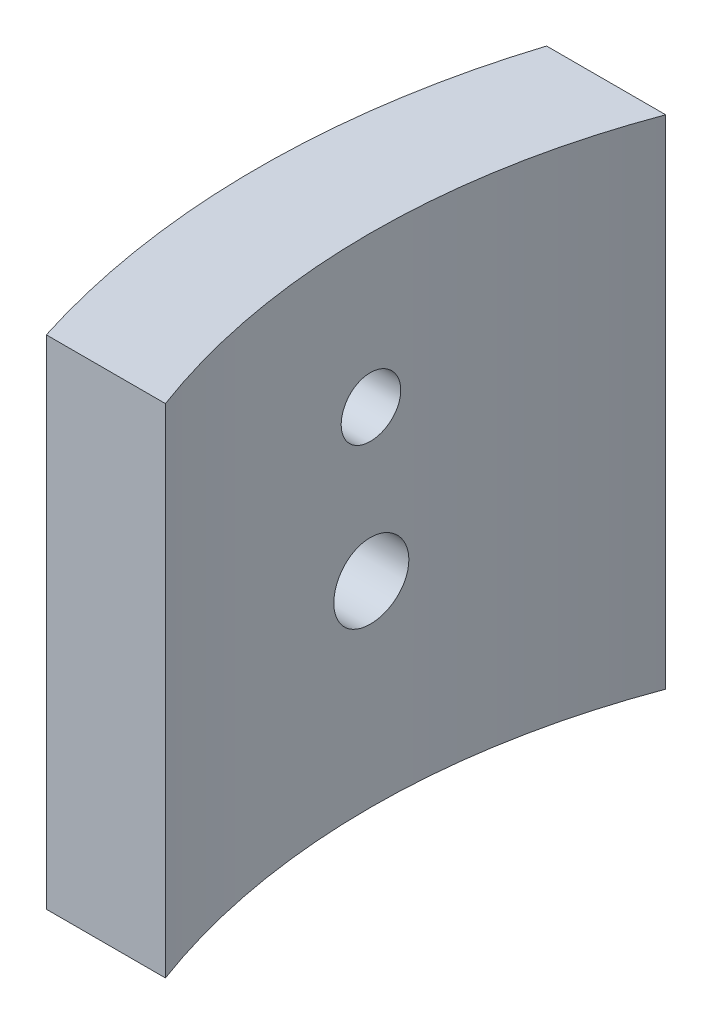
SolidWorks part; units mm, degrees
material "ABS"
ref_plane "Front Plane" through (0, 0, 0) normal (0, 0, 1) x (1, 0, 0)
ref_plane "Top Plane" through (0, 0, 0) normal (0, 1, 0) x (1, 0, 0)
ref_plane "Right Plane" through (0, 0, 0) normal (1, 0, 0) x (0, 0, -1)
sketch "Sketch1" plane through (0, 0, 0) normal (0, 1, 0) x (1, 0, 0)
  line L0 (-42.0402, -13.335) -> (-35.6902, -13.335)
  line L1 (-42.0402, 13.335) -> (-35.6902, 13.335)
  line L2 (-35.6902, 13.335) -> (0, 0) construction
  line L3 (0, 0) -> (-35.6902, -13.335) construction
  line L4 (-88.519, 13.335) -> (-35.6902, 13.335) construction
  arc A0 (-35.6902, 13.335) -> (-35.6902, -13.335) centre (0, 0) ccw
  arc A1 (-42.0402, 13.335) -> (-42.0402, -13.335) centre (0, 0) ccw
  dimension "D1" = 38.1
  dimension "D2" = 6.35
extrude "Boss-Extrude1" add sketch "Sketch1" along normal blind 38.1
ref_plane "Plane1" through (-42.0402, 0, 0) normal (-1, 0, 0) x (0, 0, 1)
sketch "Sketch2" plane through (-42.0402, 0, 0) normal (-1, 0, 0) x (0, 0, 1)
  line L0 (0, 38.1) -> (0, 0) construction
  line L1 (13.335, 38.1) -> (-13.335, 38.1) construction
  circle A0 centre (0, 30.0704) radius 1.5875
  circle A1 centre (0, 30.0704) radius 4.7625
  circle A2 centre (0, 30.0704) radius 1.5875 construction
  dimension "D1" = 3.175
extrude "Boss-Extrude3" add sketch "Sketch2" along normal up to surface (2.4098 mm away)
ref_plane "Plane2" through (-44.1044, 0, 0) normal (-1, 0, 0) x (0, 0, 1)
ref_plane "Plane3" through (-50.4544, 0, 0) normal (-1, 0, 0) x (0, 0, 1)
sketch "Sketch3" plane through (0, 0, 0) normal (0, -1, 0) x (1, 0, 0)
  line L0 (-42.0402, 13.335) -> (-35.6902, 13.335)
  line L1 (-42.0402, -13.335) -> (-35.6902, -13.335)
  arc A0 (-42.0402, 13.335) -> (-42.0402, -13.335) centre (0, 0) ccw
  arc A1 (-35.6902, -13.335) -> (-35.6902, 13.335) centre (0, 0) cw
  arc A2 (-42.0402, 13.335) -> (-42.0402, -13.335) centre (0, 0) ccw construction
  arc A3 (-35.6902, 13.335) -> (-35.6902, -13.335) centre (0, 0) ccw construction
extrude "Cut-Extrude1" cut sketch "Sketch3" against normal up to surface (11.5792 mm away)
sketch "Sketch5" plane through (-44.45, 0, 0) normal (-1, 0, 0) x (0, 0, 1)
  circle A0 centre (0, 30.0704) radius 1.5875
  circle A1 centre (0, 30.0704) radius 1.5875 construction
extrude "Cut-Extrude4" cut sketch "Sketch5" against normal through all
ref_plane "Plane4" through (-35.6902, 0, 0) normal (1, 0, 0) x (0, 0, -1)
sketch "Sketch6" plane through (-35.6902, 0, 0) normal (1, 0, 0) x (0, 0, -1)
  circle A0 centre (0, 22.0454) radius 2
  dimension "D1" = 4
extrude "Cut-Extrude5" cut sketch "Sketch6" against normal up to surface (8.3689 mm away)
